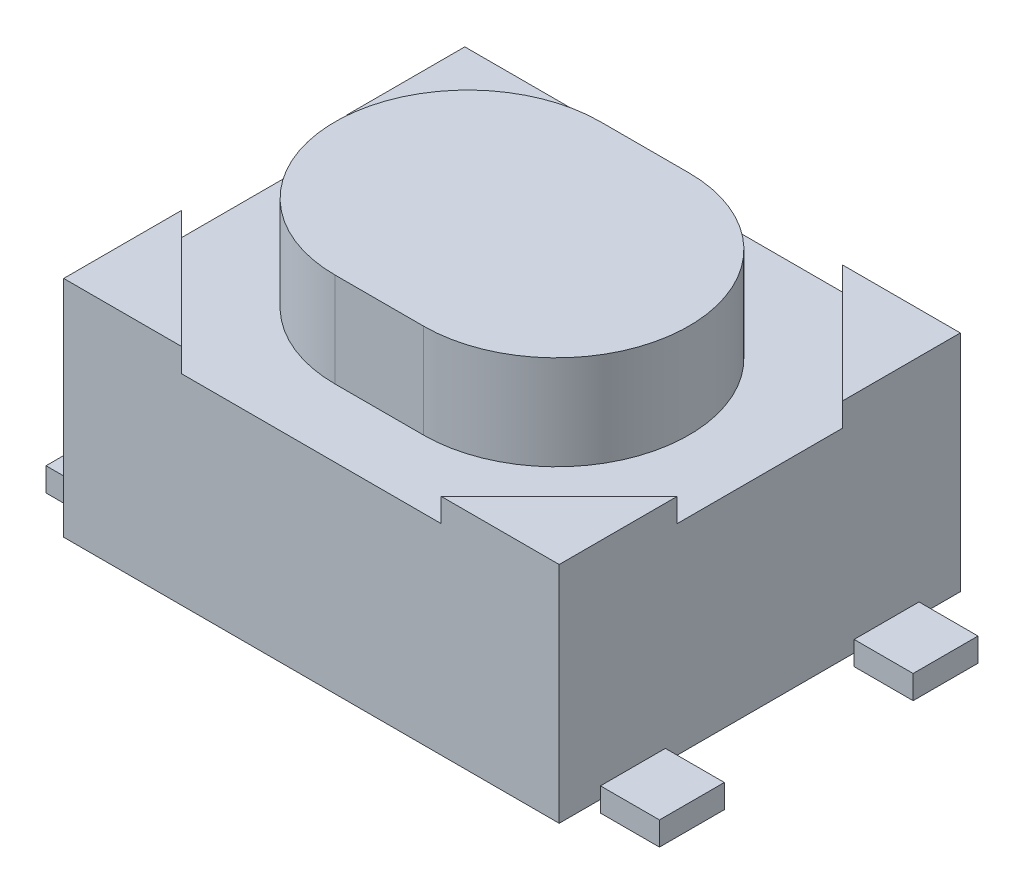
SolidWorks part; units mm, degrees
ref_plane "Front Plane" through (0, 0, 0) normal (0, 0, 1) x (1, 0, 0)
ref_plane "Top Plane" through (0, 0, 0) normal (0, 1, 0) x (1, 0, 0)
ref_plane "Right Plane" through (0, 0, 0) normal (1, 0, 0) x (0, 0, -1)
other "Center of Mass"
sketch "Sketch1" plane through (0, 0, 0) normal (0, 1, 0) x (1, 0, 0)
  line L1 (-2.1, 1.7) -> (2.1, 1.7)
  line L2 (-2.1, 1.7) -> (-2.1, -1.7)
  line L3 (-2.1, -1.7) -> (2.1, -1.7)
  line L4 (2.1, 1.7) -> (2.1, -1.7)
  line L5 (-2.1, 1.7) -> (2.1, -1.7) construction
  line L6 (-2.1, -1.7) -> (2.1, 1.7) construction
  point P0 (0, 0)
  dimension "D1" = 4.2
  dimension "D2" = 3.4
extrude "Boss-Extrude1" add sketch "Sketch1" along normal blind 1.7
sketch "Sketch2" plane through (0, 0, 0) normal (0, -1, 0) x (1, 0, 0)
  line L0 (-2.1, 0) -> (2.1, 0) construction
  line L1 (-2.1, -1.7) -> (-2.1, 1.7) construction
  line L2 (2.1, 1.7) -> (2.1, -1.7) construction
  line L3 (0, 1.7) -> (0, -1.7) construction
  line L4 (2.1, 0.8) -> (2.6, 0.8)
  line L5 (2.1, 0.8) -> (2.1, 1.35)
  line L6 (2.1, 1.35) -> (2.6, 1.35)
  line L7 (2.6, 0.8) -> (2.6, 1.35)
  line L8 (2.1, -0.8) -> (2.6, -0.8)
  line L9 (2.1, -0.8) -> (2.1, -1.35)
  line L10 (2.1, -1.35) -> (2.6, -1.35)
  line L11 (2.6, -0.8) -> (2.6, -1.35)
  line L12 (-2.1, -1.35) -> (-2.6, -1.35)
  line L13 (-2.1, -1.35) -> (-2.1, -0.8)
  line L14 (-2.1, -0.8) -> (-2.6, -0.8)
  line L15 (-2.6, -1.35) -> (-2.6, -0.8)
  line L16 (-2.1, 0.8) -> (-2.6, 0.8)
  line L17 (-2.1, 0.8) -> (-2.1, 1.35)
  line L18 (-2.1, 1.35) -> (-2.6, 1.35)
  line L19 (-2.6, 0.8) -> (-2.6, 1.35)
  line L20 (-2.1, 1.7) -> (2.1, 1.7) construction
  line L21 (2.1, -1.7) -> (-2.1, -1.7) construction
  point P28 (-2.35, 1.35)
  dimension "D1" = 2.6
  dimension "D2" = 2.6
  dimension "D3" = 2.6
  dimension "D4" = 2.6
  dimension "D5" = 0.55
  dimension "D6" = 0.55
  dimension "D7" = 0.55
  dimension "D8" = 0.55
  dimension "D9" = 1.35
  dimension "D10" = 1.35
  dimension "D11" = 1.35
  dimension "D12" = 1.35
extrude "Boss-Extrude2" add sketch "Sketch2" along normal mid plane 0.2
sketch "Sketch3" plane through (0, 1.7, 0) normal (0, 1, 0) x (1, 0, 0)
  line L0 (-2.1, 1.7) -> (-1.1, 1.7)
  line L1 (2.1, 1.7) -> (-2.1, 1.7) construction
  line L2 (-1.1, 1.7) -> (-2.1, 0.7)
  line L3 (-2.1, 1.35) -> (-2.1, 0.8) construction
  line L4 (-2.1, 0.7) -> (-2.1, 1.7)
  line L5 (1.1, 1.7) -> (2.1, 0.7)
  line L6 (2.1, -1.7) -> (2.1, 1.7) construction
  line L7 (2.1, 0.7) -> (2.1, 1.7)
  line L8 (2.1, 1.7) -> (1.1, 1.7)
  line L9 (-2.1, -0.7) -> (-1.1, -1.7)
  line L10 (-2.1, 1.7) -> (-2.1, -1.7) construction
  line L11 (-2.1, -1.7) -> (2.1, -1.7) construction
  line L12 (-1.1, -1.7) -> (-2.1, -1.7)
  line L13 (-2.1, -1.7) -> (-2.1, -0.7)
  line L14 (1.1, -1.7) -> (2.1, -0.7)
  line L15 (2.1, -0.7) -> (2.1, -1.7)
  line L16 (2.1, -1.7) -> (1.1, -1.7)
  dimension "D1" = 1
  dimension "D2" = 1
  dimension "D3" = 1
  dimension "D4" = 1
  dimension "D5" = 1
  dimension "D6" = 1
  dimension "D7" = 1
  dimension "D8" = 1
extrude "Boss-Extrude3" add sketch "Sketch3" along normal blind 0.2
sketch "Sketch4" plane through (0, 1.7, 0) normal (0, 1, 0) x (1, 0, 0)
  line L0 (0, 1.7) -> (0, -1.7) construction
  line L1 (1.1, 1.7) -> (-1.1, 1.7) construction
  line L2 (-1.1, -1.7) -> (1.1, -1.7) construction
  line L3 (-2.1, 0) -> (2.1, 0) construction
  line L4 (-2.1, 0.7) -> (-2.1, -0.7) construction
  line L5 (2.1, -0.7) -> (2.1, 0.7) construction
  line L6 (1.5, 0) -> (1.5, 0.5632) construction
  line L7 (-1.5, 0) -> (-1.5, 0.6275) construction
  line L9 (-0.375, 1.125) -> (0.375, 1.125)
  line L10 (-0.375, 1.125) -> (-0.375, -1.125)
  line L11 (-0.375, -1.125) -> (0.375, -1.125)
  line L12 (0.375, 1.125) -> (0.375, -1.125)
  circle A0 centre (0.375, 0) radius 1.125
  circle A1 centre (-0.375, 0) radius 1.125
  dimension "D3" = 2.25
  dimension "D4" = 2.25
  dimension "D1" = 1.5
  dimension "D2" = 1.5
extrude "Boss-Extrude4" add sketch "Sketch4" along normal blind 0.8 contours A1 A0 L9 | A1 L11 A0 | A0 A1 L12 L10 | A1 L12 A0 | A0 A1 L10 | A1 A0 L12 | L10 A1 A0 | L12 A1 | L10 A0 | A1 L12 A0 | L10 A1 A0
